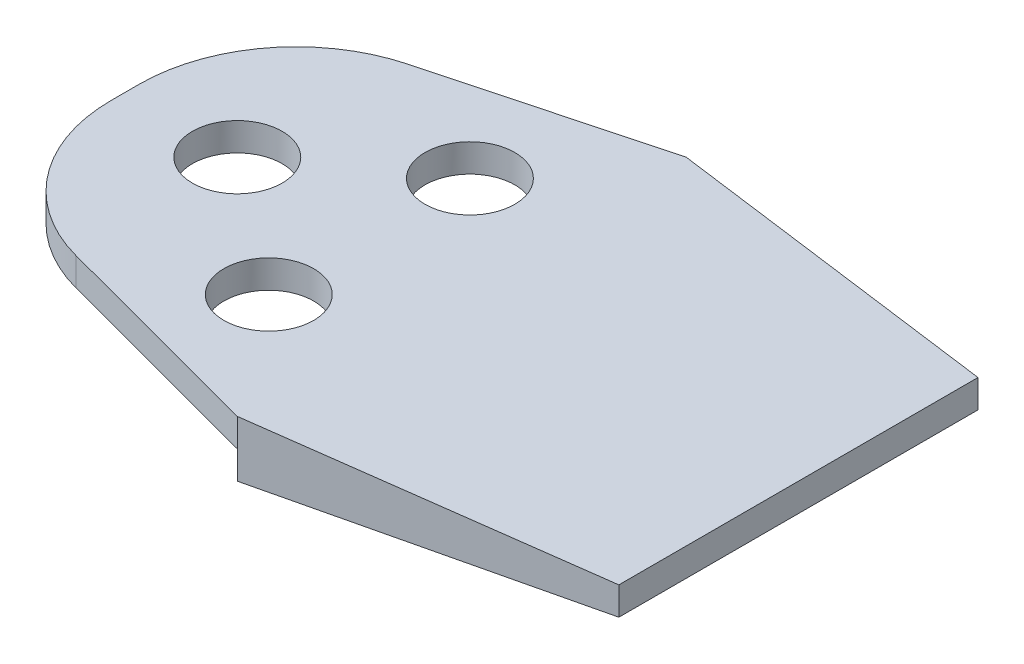
SolidWorks part; units mm, degrees
ref_plane "Front Plane" through (0, 0, 0) normal (0, 0, 1) x (1, 0, 0)
ref_plane "Top Plane" through (0, 0, 0) normal (0, 1, 0) x (1, 0, 0)
ref_plane "Right Plane" through (0, 0, 0) normal (1, 0, 0) x (0, 0, -1)
sketch "Sketch1" plane through (0, 0, 0) normal (0, 0, 1) x (1, 0, 0)
  line L0 (-19.05, 0) -> (19.05, 0)
  line L1 (55, 0) -> (-55, 0) construction
  line L2 (19.05, 0) -> (19.05, -1.5875)
  line L3 (19.05, -1.5875) -> (0, -3.175)
  line L4 (0, -55) -> (0, 55) construction
  line L5 (0, -3.175) -> (0, -1.5875)
  line L6 (0, -1.5875) -> (-19.05, -1.5875)
  line L7 (-19.05, -1.5875) -> (-19.05, 0)
  dimension "D1" = 1.5875
  dimension "D2" = 1.5875
  dimension "D3" = 1.5875
  dimension "D4" = 19.05
  dimension "D5" = 19.05
extrude "Boss-Extrude1" add sketch "Sketch1" along normal mid plane 25.4
sketch "Sketch2" plane through (0, 0, 0) normal (0, 1, 0) x (1, 0, 0)
  line L0 (0, 12.7) -> (19.05, 10.16)
  line L1 (19.05, 12.7) -> (-19.05, 12.7) construction
  line L2 (19.05, -12.7) -> (19.05, 12.7) construction
  line L3 (19.05, 10.16) -> (19.05, 12.7)
  line L4 (19.05, 12.7) -> (0, 12.7)
  dimension "D1" = 2.54
extrude "Cut-Extrude1" cut sketch "Sketch2" against normal blind 25.4
mirror "Mirror1" about plane through (0, 0, 0) normal (0, 0, 1) of "Cut-Extrude1"
sketch "Sketch3" plane through (0, 0, 0) normal (0, 1, 0) x (1, 0, 0)
  line L0 (0, 12.7) -> (-19.05, 7.62)
  line L1 (0, -1.7462) -> (0, 1.7462) construction
  line L2 (0, 12.7) -> (-19.05, 12.7) construction
  line L3 (-19.05, -12.7) -> (-19.05, 12.7) construction
  line L4 (-19.05, 7.62) -> (-19.05, 12.7)
  line L5 (-19.05, 12.7) -> (0, 12.7)
  dimension "D1" = 5.08
extrude "Cut-Extrude2" cut sketch "Sketch3" against normal blind 25.4
mirror "Mirror2" about plane through (0, 0, 0) normal (0, 0, 1) of "Cut-Extrude2"
fillet "Fillet1" radius 8.89 2 edges at (-19.05, -0.7937, 7.62) (-19.05, -0.7937, -7.62)
sketch "Sketch4" plane through (0, 0, 0) normal (0, 1, 0) x (1, 0, 0)
  line L0 (-1.7462, 0) -> (1.7462, 0) construction
  line L1 (0, -1.7462) -> (0, 1.7462) construction
  line L2 (-19.05, -0.79) -> (-19.05, 0.79) construction
  circle A0 centre (-5.08, 5.5434) radius 2.54
  circle A1 centre (-5.08, -5.8377) radius 2.54
  circle A2 centre (-12.7, 0) radius 2.54
  dimension "D3" = 5.08
  dimension "D4" = 5.08
  dimension "D5" = 5.08
  dimension "D1" = 5.08
  dimension "D2" = 5.08
  dimension "D6" = 6.35
extrude "Cut-Extrude3" cut sketch "Sketch4" against normal blind 25.4
